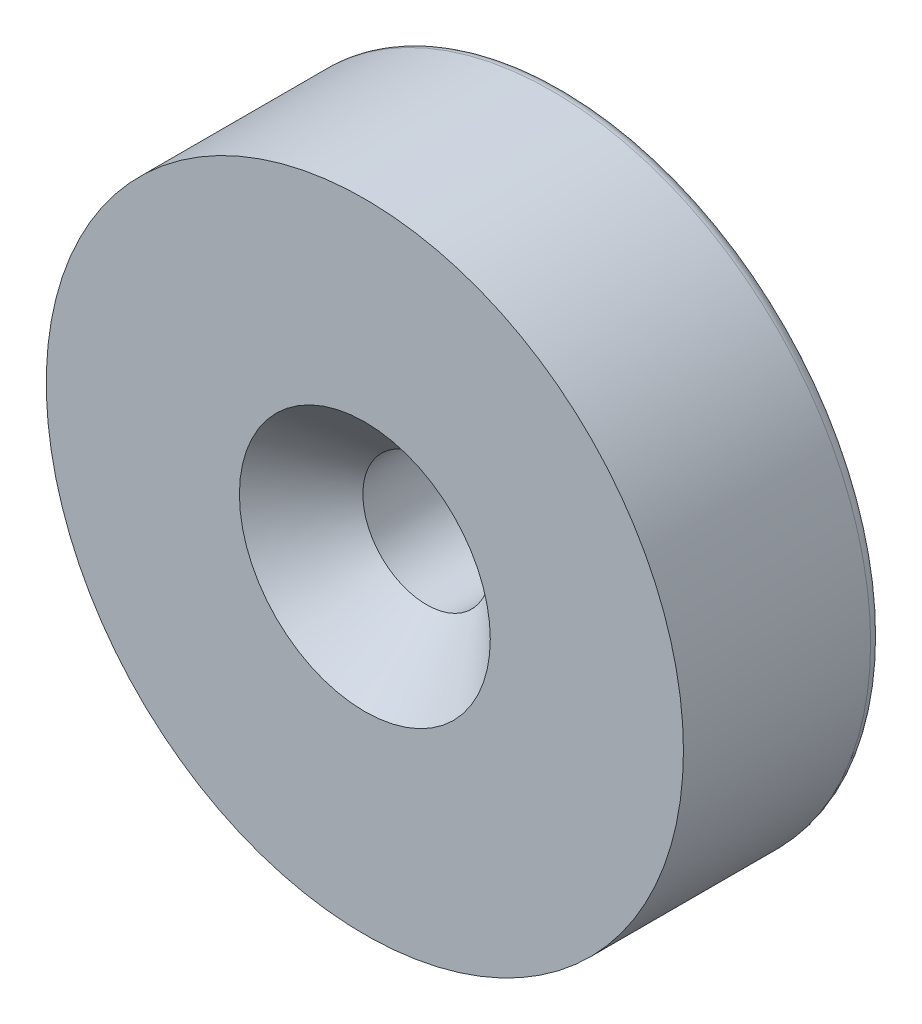
SolidWorks part; units mm, degrees
ref_plane "Front" through (0, 0, 0) normal (0, 0, 1) x (1, 0, 0)
ref_plane "Top" through (0, 0, 0) normal (0, 1, 0) x (1, 0, 0)
ref_plane "Right" through (0, 0, 0) normal (1, 0, 0) x (0, 0, -1)
sketch "Esboço1" plane through (0, 0, 0) normal (0, 0, 1) x (1, 0, 0)
  circle A0 centre (0, 0) radius 8
  dimension "D1" = 16
extrude "Ressalto-extrusão1" add sketch "Esboço1" along normal blind 5
hole_wizard "Formsenkung für M3 Linsensenkschraube mit Schlitz1" positions "3DSketch1" profile "Esboço2" countersink size "M3" standard "DIN"
sketch3d "3DSketch1"
  point P0 (0, 0, 5)
sketch "Esboço2" plane through (0, 0, 5) normal (1, 0, 0) x (0, -1, 0)
  line L0 (0, 0) -> (0, 21.8314)
  line L1 (0, 21.8314) -> (1.6, 20.87)
  line L2 (1.6, 20.87) -> (1.6, 1.55)
  line L3 (1.6, 1.55) -> (3.15, 0)
  line L5 (3.15, 0) -> (0, 0)
  line L6 (-1.6, 1.55) -> (-3.15, 0) construction
  line L10 (0, 21.8314) -> (-1.6, 20.87) construction
  line L11 (0, -6.35) -> (0, 107.95) construction
  dimension "Hole Dia." = 3.2
  dimension "Hole Depth" = 20.87
  dimension "Near C'Sink Dia." = 6.3
  dimension "Near C'Sink Angle" = 90
  dimension "Drill Angle" = 118
fillet "Filete1" radius 0.3 1 edges at (8, 0, 0)
